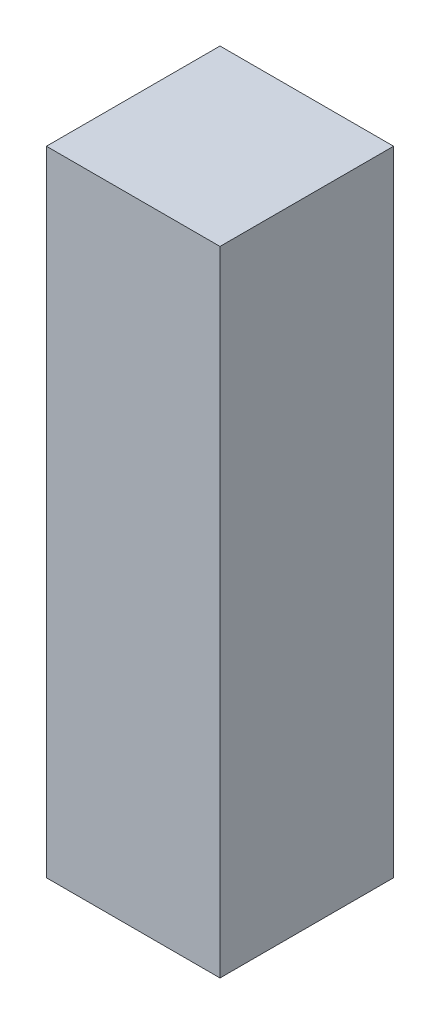
SolidWorks part; units mm, degrees
ref_plane "前视基准面" through (0, 0, 0) normal (0, 0, 1) x (1, 0, 0)
ref_plane "上视基准面" through (0, 0, 0) normal (0, 1, 0) x (1, 0, 0)
ref_plane "右视基准面" through (0, 0, 0) normal (1, 0, 0) x (0, 0, -1)
other "Configuration Table"
sketch "草图1" plane through (0, 0, 0) normal (0, 1, 0) x (1, 0, 0)
  line L1 (-10, 10) -> (10, 10)
  line L2 (-10, 10) -> (-10, -10)
  line L3 (-10, -10) -> (10, -10)
  line L4 (10, 10) -> (10, -10)
  line L5 (-10, 10) -> (10, -10) construction
  line L6 (-10, -10) -> (10, 10) construction
  point P0 (0, 0)
  dimension "D1" = 20
  dimension "D2" = 20
extrude "凸台-拉伸1" add sketch "草图1" along normal blind 73
